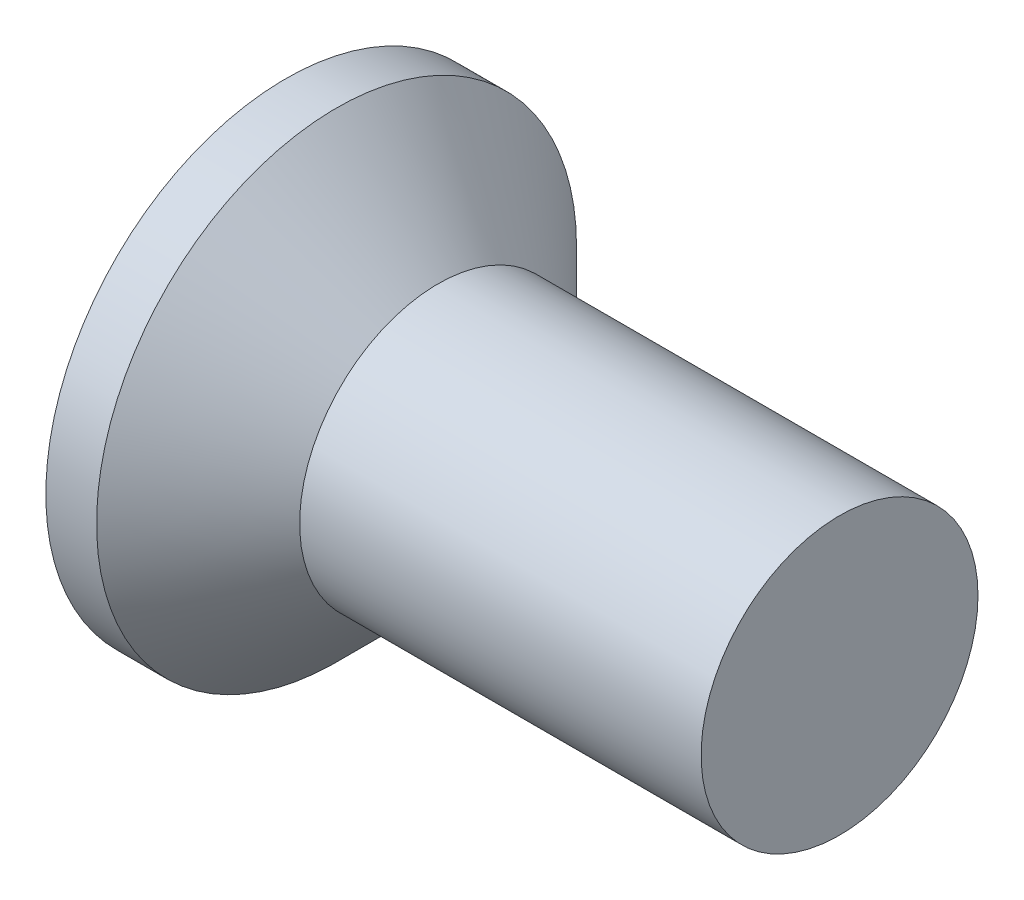
SolidWorks part; units mm, degrees
ref_plane "Front" through (0, 0, 0) normal (0, 0, 1) x (1, 0, 0)
ref_plane "Top" through (0, 0, 0) normal (0, 1, 0) x (1, 0, 0)
ref_plane "Right" through (0, 0, 0) normal (1, 0, 0) x (0, 0, -1)
sketch "Sketch1" plane through (0, 0, 0) normal (0, 0, 1) x (1, 0, 0)
  line L0 (6, 1.5) -> (2.65, 1.5)
  line L1 (2.65, 1.5) -> (1.65, 1.5)
  line L2 (1.65, 1.5) -> (0.55, 2.6)
  line L3 (0.55, 2.6) -> (0, 2.6)
  line L4 (6, 1.5) -> (6, 0)
  line L5 (4.5158, 0) -> (-89.8219, 0) construction
  line L6 (6, 0) -> (0, 0)
  line L7 (0, 2.6) -> (0, 0)
  dimension "D1" = 45
  dimension "d" = 3
  dimension "dk" = 5.2
  dimension "l" = 6
  dimension "k" = 1.65
  dimension "a" = 1
revolve "Base" add sketch "Sketch1" angle 360 about L5
cosmetic thread "ThreadCosmetic1" [suppressed] parameters "bb"=4.35, "THD_MINOR"=2.459
sketch "Sketch6" plane through (0, 0, 0) normal (1, 0, 0) x (0, 0, -1)
  line L0 (-1.9271, 0) -> (2.0512, 0) construction
  line L1 (0, 1.8651) -> (0, -2.0207) construction
  line L2 (0.32, 0.32) -> (0.32, 1.6)
  line L3 (0.32, 1.6) -> (-0.32, 1.6)
  line L4 (-0.32, 0.32) -> (-0.32, 1.6)
  line L5 (0.32, 0.32) -> (1.6, 0.32)
  line L6 (1.6, 0.32) -> (1.6, -0.32)
  line L7 (-1.6, 0.32) -> (-1.6, -0.32)
  line L8 (-0.32, 0.32) -> (-1.6, 0.32)
  line L9 (-0.32, -0.32) -> (-1.6, -0.32)
  line L10 (0.32, -0.32) -> (1.6, -0.32)
  line L11 (-0.32, -0.32) -> (-0.32, -1.6)
  line L12 (0.32, -1.6) -> (-0.32, -1.6)
  line L13 (0.32, -0.32) -> (0.32, -1.6)
  point P16 (-1.6, 0)
  point P17 (1.6, 0)
  dimension "D1" = 0.64
  dimension "m" = 3.2
extrude "CrossRecess" cut sketch "Sketch6" along normal blind 0.825
draft "Draft9" type of draft neutral plane draft angle 30 faces to draft 4 face at (0.4125, 1.6, 0) face at (0.4125, 0, 1.6) face at (0.4125, -1.6, 0) face at (0.4125, 0, -1.6) neutral plane through (0, 2.6, 0) neutral plane normal (-1, 0, 0) parameters "D1"=30
fillet "Fillet5" radius 0.3 4 edges at (0.4125, -0.32, -0.32) (0.4125, 0.32, -0.32) (0.4125, 0.32, 0.32) (0.4125, -0.32, 0.32)
sketch "Sketch7" plane through (0, 0, 0) normal (1, 0, 0) x (0, 0, -1)
  line L0 (-2.0126, 0) -> (1.9757, 0) construction
  line L1 (0, 1.9314) -> (0, -2.0126) construction
  line L2 (0, 0) -> (1.5555, 1.5555) construction
  line L3 (0, 0.4782) -> (1.1314, 1.1314)
  line L4 (-1.5402, 1.5402) -> (0, 0) construction
  line L5 (0.4782, 0) -> (1.1314, 1.1314)
  line L6 (0, -0.4782) -> (1.1314, -1.1314)
  line L7 (0.4782, 0) -> (1.1314, -1.1314)
  line L8 (-0.4782, 0) -> (-1.1314, -1.1314)
  line L9 (0, -0.4782) -> (-1.1314, -1.1314)
  line L10 (-0.4782, 0) -> (-1.1314, 1.1314)
  line L11 (0, 0.4782) -> (-1.1314, 1.1314)
  dimension "D3" = 15
extrude "Cut-Extrude3" [suppressed] cut sketch "Sketch7" along normal blind 10 draft 20
sketch "Sketch8" plane through (0, 0, 0) normal (0, 0, 1) x (1, 0, 0)
  line L0 (-19, 1.7705) -> (-20.25, 1.5)
  line L1 (-20.25, 1.5) -> (1.65, 1.5)
  line L3 (6, -1.5) -> (6, 1.5) construction
  line L6 (1.65, 1.5) -> (1.65, 6.5)
  line L7 (1.65, 6.5) -> (-19, 6.5)
  line L8 (-19, 6.5) -> (-19, 1.7705)
  line L9 (62.4753, 0.2705) -> (52.9594, 0.2705) construction
  dimension "D1" = 5
  dimension "x" = 1.25
  dimension "b" = 25
sketch "Sketch9" plane through (0, 0, 0) normal (0, 0, 1) x (1, 0, 0)
  line L0 (6, 1.2657) -> (6.1352, 1.5)
  line L1 (6.1352, 1.5) -> (6.1352, 1.7705)
  line L2 (6.1352, 1.7705) -> (5.8647, 1.7705)
  line L3 (5.8647, 1.7705) -> (5.8647, 1.5)
  line L4 (5.8647, 1.5) -> (6, 1.2657)
  line L5 (0, 0) -> (73.843, 0) construction
  line L6 (6, -1.5) -> (6, 1.5) construction
  dimension "D1" = 3
  dimension "D2" = 0.2705
revolve "Cut-Revolve10" [suppressed] cut sketch "Sketch9" angle 360 about L5
pattern_linear "LPattern10" [suppressed] count 13 spacing 0.3246 along (1, 0, 0)
equation "\"D1@Sketch6\" = \"m@Sketch6\" / 5"
equation "\"D1@CrossRecess\" = \"k@Sketch1\" / 2"
equation "\"D1@Sketch9\" = \"d@Sketch1\""
equation "\"D2@Sketch9\" =  ( \"d@Sketch1\" - \"THD_MINOR@ThreadCosmetic1\" )  / 2"
equation "\"D3@LPattern10\" = \"D2@Sketch9\" * 1.2"
equation "\"D1@LPattern10\" = \"bb@ThreadCosmetic1\" / \"D3@LPattern10\" "
